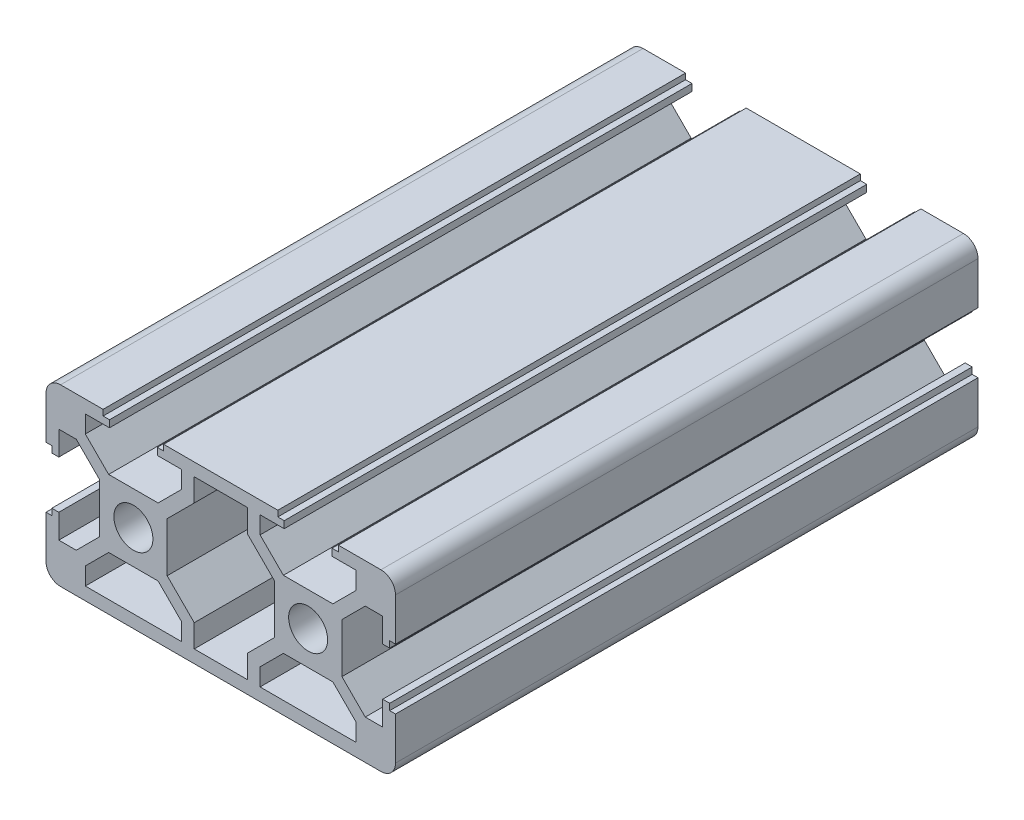
SolidWorks part; units mm, degrees
ref_plane "前视基准面" through (0, 0, 0) normal (0, 0, 1) x (1, 0, 0)
ref_plane "上视基准面" through (0, 0, 0) normal (0, 1, 0) x (1, 0, 0)
ref_plane "右视基准面" through (0, 0, 0) normal (1, 0, 0) x (0, 0, -1)
sketch "草图1" plane through (0, 0, 0) normal (0, 0, 1) x (1, 0, 0)
  line B0 (38.25, -9.8056) -> (34.2444, -5.8)
  line B1 (34.2444, -5.8) -> (25.7556, -5.8)
  line B2 (25.7556, -5.8) -> (21.75, -9.8056)
  line B3 (21.75, -9.8056) -> (21.75, -12.8)
  line B4 (21.75, -12.8) -> (38.25, -12.8)
  line B5 (38.25, -12.8) -> (38.25, -9.8056)
  line B6 (-5.8, -4.2444) -> (-9.8056, -8.25)
  line B7 (-9.8056, -8.25) -> (-12.8, -8.25)
  line B8 (-12.8, -8.25) -> (-12.8, -4.1)
  line B9 (-12.8, -4.1) -> (-14, -4.1)
  line B10 (-14, -4.1) -> (-14, -5.2)
  line B11 (-14, -5.2) -> (-15, -5.2)
  line B12 (-15, -5.2) -> (-15, -12.5)
  line B13 (-12.5, -15) -> (42.5, -15)
  line B14 (45, -12.5) -> (45, -5.2)
  line B15 (45, -5.2) -> (44, -5.2)
  line B16 (44, -5.2) -> (44, -4.1)
  line B17 (44, -4.1) -> (42.8, -4.1)
  line B18 (42.8, -4.1) -> (42.8, -8.25)
  line B19 (42.8, -8.25) -> (39.8056, -8.25)
  line B20 (39.8056, -8.25) -> (35.8, -4.2444)
  line B21 (35.8, -4.2444) -> (35.8, 4.2444)
  line B22 (35.8, 4.2444) -> (39.8056, 8.25)
  line B23 (39.8056, 8.25) -> (42.8, 8.25)
  line B24 (42.8, 8.25) -> (42.8, 4.1)
  line B25 (42.8, 4.1) -> (44, 4.1)
  line B26 (44, 4.1) -> (44, 5.2)
  line B27 (44, 5.2) -> (45, 5.2)
  line B28 (45, 5.2) -> (45, 12.5)
  line B29 (42.5, 15) -> (35.2, 15)
  line B30 (35.2, 15) -> (35.2, 14)
  line B31 (35.2, 14) -> (34.1, 14)
  line B32 (34.1, 14) -> (34.1, 12.8)
  line B33 (34.1, 12.8) -> (38.25, 12.8)
  line B34 (38.25, 12.8) -> (38.25, 9.8056)
  line B35 (38.25, 9.8056) -> (34.2444, 5.8)
  line B36 (34.2444, 5.8) -> (25.7556, 5.8)
  line B37 (25.7556, 5.8) -> (21.75, 9.8056)
  line B38 (21.75, 9.8056) -> (21.75, 12.8)
  line B39 (21.75, 12.8) -> (25.9, 12.8)
  line B40 (25.9, 12.8) -> (25.9, 14)
  line B41 (25.9, 14) -> (24.8, 14)
  line B42 (24.8, 14) -> (24.8, 15)
  line B43 (24.8, 15) -> (5.2, 15)
  line B44 (5.2, 15) -> (5.2, 14)
  line B45 (5.2, 14) -> (4.1, 14)
  line B46 (4.1, 14) -> (4.1, 12.8)
  line B47 (4.1, 12.8) -> (8.25, 12.8)
  line B48 (8.25, 12.8) -> (8.25, 9.8056)
  line B49 (8.25, 9.8056) -> (4.2444, 5.8)
  line B50 (4.2444, 5.8) -> (-4.2444, 5.8)
  line B51 (-4.2444, 5.8) -> (-8.25, 9.8056)
  line B52 (-8.25, 9.8056) -> (-8.25, 12.8)
  line B53 (-8.25, 12.8) -> (-4.1, 12.8)
  line B54 (-4.1, 12.8) -> (-4.1, 14)
  line B55 (-4.1, 14) -> (-5.2, 14)
  line B56 (-5.2, 14) -> (-5.2, 15)
  line B57 (-5.2, 15) -> (-12.5, 15)
  line B58 (-15, 12.5) -> (-15, 5.2)
  line B59 (-15, 5.2) -> (-14, 5.2)
  line B60 (-14, 5.2) -> (-14, 4.1)
  line B61 (-14, 4.1) -> (-12.8, 4.1)
  line B62 (-12.8, 4.1) -> (-12.8, 8.25)
  line B63 (-12.8, 8.25) -> (-9.8056, 8.25)
  line B64 (-9.8056, 8.25) -> (-5.8, 4.2444)
  line B65 (-5.8, 4.2444) -> (-5.8, -4.2444)
  line B66 (8.25, -9.8056) -> (4.2444, -5.8)
  line B67 (4.2444, -5.8) -> (-4.2444, -5.8)
  line B68 (-4.2444, -5.8) -> (-8.25, -9.8056)
  line B69 (-8.25, -9.8056) -> (-8.25, -12.8)
  line B70 (-8.25, -12.8) -> (8.25, -12.8)
  line B71 (8.25, -12.8) -> (8.25, -9.8056)
  line B72 (19.55, 12.8) -> (10.45, 12.8)
  line B73 (10.45, 12.8) -> (10.45, 8.8944)
  line B74 (10.45, 8.8944) -> (5.8, 4.2444)
  line B75 (5.8, 4.2444) -> (5.8, -4.2444)
  line B76 (5.8, -4.2444) -> (10.45, -8.8944)
  line B77 (10.45, -8.8944) -> (10.45, -12.8)
  line B78 (10.45, -12.8) -> (19.55, -12.8)
  line B79 (19.55, -12.8) -> (19.55, -8.8944)
  line B80 (19.55, -8.8944) -> (24.2, -4.2444)
  line B81 (24.2, -4.2444) -> (24.2, 4.2444)
  line B82 (24.2, 4.2444) -> (19.55, 8.8944)
  line B83 (19.55, 8.8944) -> (19.55, 12.8)
  arc B84 (-15, -12.5) -> (-12.5, -15) centre (-12.5, -12.5) ccw
  arc B85 (42.5, -15) -> (45, -12.5) centre (42.5, -12.5) ccw
  arc B86 (45, 12.5) -> (42.5, 15) centre (42.5, 12.5) ccw
  arc B87 (-12.5, 15) -> (-15, 12.5) centre (-12.5, 12.5) ccw
  circle B88 centre (30, 0) radius 3.35
  circle B89 centre (0, 0) radius 3.35
sketch_block_instance "A$C0DB829E0-1"
sketch_block "A$C0DB829E0"
extrude "凸台-拉伸1" add sketch "草图1" along normal blind 100
